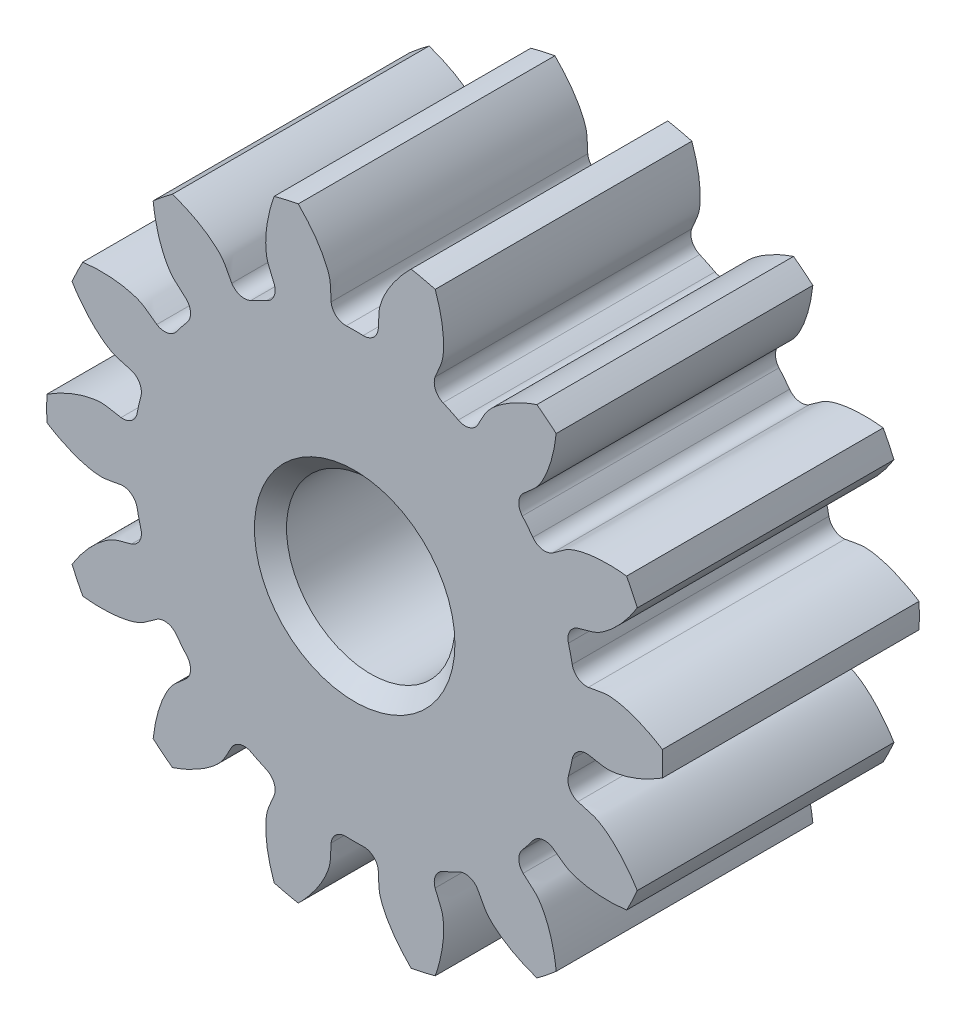
SolidWorks part; units mm, degrees
ref_plane "Front Plane" through (0, 0, 0) normal (0, 0, 1) x (1, 0, 0)
ref_plane "Top Plane" through (0, 0, 0) normal (0, 1, 0) x (1, 0, 0)
ref_plane "Right Plane" through (0, 0, 0) normal (1, 0, 0) x (0, 0, -1)
ref_axis "Axis1" through (0, 0, -88.99) along (0, 0, 1)
sketch "Sketch1" plane through (0, 0, 0) normal (0, 0, 1) x (1, 0, 0)
  circle A0 centre (0, 0) radius 9.6
extrude "LaShenA" add sketch "Sketch1" along normal blind 8
sketch "SketchA" plane through (0, 0, 8) normal (0, 0, 1) x (1, 0, 0)
  line L0 (0, 0) -> (0, 9.6) construction
  arc A0 (0.2639, 6.895) -> (-0.2639, 6.895) centre (0, 0) ccw
  arc A1 (2.4844, 10.0489) -> (-2.4844, 10.0489) centre (0, 0) ccw
  arc A2 (-0.2639, 6.895) -> (-0.7348, 7.3025) centre (-0.2814, 7.3506) cw
  arc A3 (0.7348, 7.3025) -> (0.2639, 6.895) centre (0.2814, 7.3506) cw
  circle A4 centre (0, 0) radius 7.8934 construction
  circle A5 centre (0, 0) radius 9.6 construction
  circle A6 centre (0, 0) radius 6.9 construction
  circle A7 centre (0, 0) radius 8.4 construction
  spline S0 degree 3 poles (0.7348, 7.3025) (0.7544, 7.4871) (0.7376, 7.7039) (0.7817, 7.9284) (0.7974, 7.9855) (0.8111, 8.0306) (0.8285, 8.0821) (0.85, 8.1398) (0.8759, 8.2036) (0.9067, 8.2732) (0.9427, 8.3484) (0.9843, 8.4289) (1.0318, 8.5144) (1.0856, 8.6047) (1.146, 8.6994) (1.2133, 8.7982) (1.2878, 8.9008) (1.3699, 9.0069) (1.4597, 9.116) (1.5576, 9.2278) (1.6637, 9.3419) (1.7784, 9.4579) (1.9017, 9.5753) (2.034, 9.6938) (2.2261, 9.8557) (2.3786, 9.9726) (2.4844, 10.0489) knots 0.117633 0.117633 0.117633 0.117633 0.26174 0.285267 0.295626 0.307868 0.321993 0.338001 0.355893 0.375668 0.397327 0.420869 0.446294 0.473603 0.502795 0.53387 0.566829 0.601671 0.638396 0.677005 0.717497 0.759872 0.804131 0.850273 0.898299 1 1 1 1
  spline S1 degree 3 poles (-0.7348, 7.3025) (-0.7544, 7.4871) (-0.7376, 7.7039) (-0.7817, 7.9284) (-0.7974, 7.9855) (-0.8111, 8.0306) (-0.8285, 8.0821) (-0.85, 8.1398) (-0.8759, 8.2036) (-0.9067, 8.2732) (-0.9427, 8.3484) (-0.9843, 8.4289) (-1.0318, 8.5144) (-1.0856, 8.6047) (-1.146, 8.6994) (-1.2133, 8.7982) (-1.2878, 8.9008) (-1.3699, 9.0069) (-1.4597, 9.116) (-1.5576, 9.2278) (-1.6637, 9.3419) (-1.7784, 9.4579) (-1.9017, 9.5753) (-2.034, 9.6938) (-2.2261, 9.8557) (-2.3786, 9.9726) (-2.4844, 10.0489) knots 0.117633 0.117633 0.117633 0.117633 0.26174 0.285267 0.295626 0.307868 0.321993 0.338001 0.355893 0.375668 0.397327 0.420869 0.446294 0.473603 0.502795 0.53387 0.566829 0.601671 0.638396 0.677005 0.717497 0.759872 0.804131 0.850273 0.898299 1 1 1 1
  dimension "D1" = 0.456
  dimension "Db" = 15.7868
  dimension "Da" = 19.2
  dimension "Df" = 13.8
  dimension "Dn" = 16.8
extrude "Cut-ExtrudeA" cut sketch "SketchA" against normal blind 8
pattern_circular "www.KYTool.cn" count 14 over 360 about axis through (0, 0, -88.99) along (0, 0, 1) of "Cut-ExtrudeA"
sketch "Sketch3" plane through (0, 0, 8) normal (0, 0, 1) x (1, 0, 0)
  circle A0 centre (0, 0) radius 2.625
  dimension "D1" = 5.25
extrude "Cut-Extrude2" cut sketch "Sketch3" against normal through all
chamfer "Chamfer1" distance 0.5 angle 45 2 edges at (2.625, 0, 8) (2.625, 0, 0)
